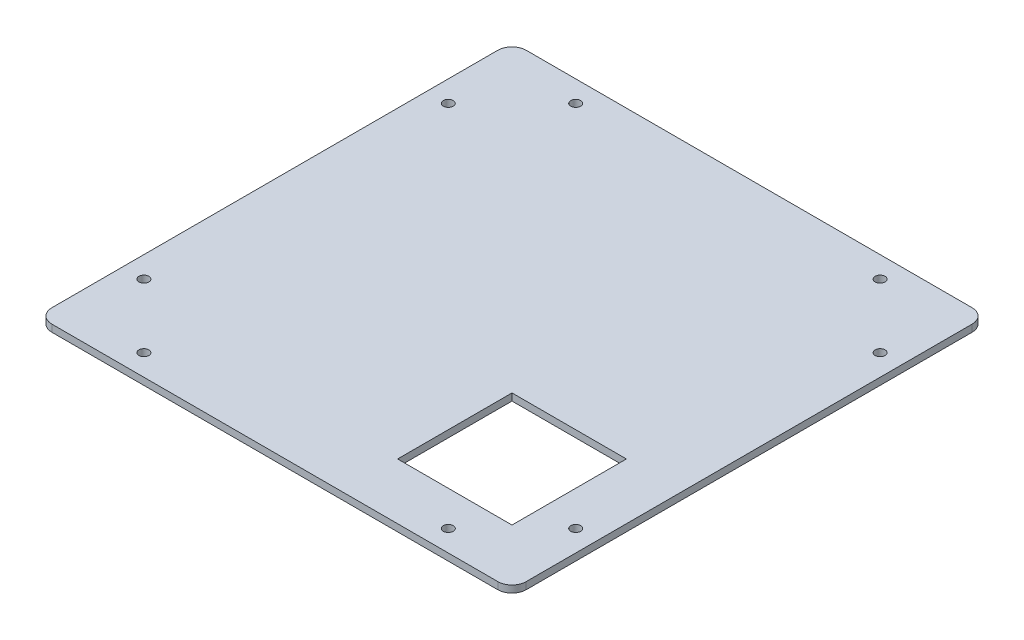
SolidWorks part; units mm, degrees
material "Acrylic (Medium-high impact)"
ref_plane "Front Plane" through (0, 0, 0) normal (0, 0, 1) x (1, 0, 0)
ref_plane "Top Plane" through (0, 0, 0) normal (0, 1, 0) x (1, 0, 0)
ref_plane "Right Plane" through (0, 0, 0) normal (1, 0, 0) x (0, 0, -1)
sketch "Sketch1" plane through (0, 0, 0) normal (0, 1, 0) x (1, 0, 0)
  line L1 (-212.725, -212.725) -> (212.725, -212.725)
  line L2 (-212.725, -212.725) -> (-212.725, 212.725)
  line L3 (-212.725, 212.725) -> (212.725, 212.725)
  line L4 (212.725, -212.725) -> (212.725, 212.725)
  line L5 (-212.725, -212.725) -> (212.725, 212.725) construction
  line L6 (-212.725, 212.725) -> (212.725, -212.725) construction
  point P0 (0, 0)
  dimension "D1" = 425.45
extrude "Boss-Extrude1" add sketch "Sketch1" along normal blind 6.35
sketch "Sketch3" plane through (0, 6.35, 0) normal (0, 1, 0) x (1, 0, 0)
  line L0 (-212.725, 212.725) -> (-212.725, -212.725) construction
  line L1 (-193.675, -193.675) -> (193.675, -193.675) construction
  line L2 (-193.675, -193.675) -> (-193.675, 193.675) construction
  line L3 (-193.675, 193.675) -> (193.675, 193.675) construction
  line L4 (193.675, -193.675) -> (193.675, 193.675) construction
  line L5 (-193.675, -193.675) -> (193.675, 193.675) construction
  line L6 (-193.675, 193.675) -> (193.675, -193.675) construction
  line L7 (212.725, 212.725) -> (-212.725, 212.725) construction
  line L8 (-212.725, -212.725) -> (212.725, -212.725) construction
  line L9 (212.725, -212.725) -> (212.725, 212.725) construction
  circle A0 centre (-193.675, 136.525) radius 8.7312
  circle A1 centre (-193.675, -136.525) radius 8.7312
  circle A2 centre (-136.525, -193.675) radius 8.7312
  circle A3 centre (136.525, -193.675) radius 8.7312
  circle A4 centre (193.675, -136.525) radius 8.7313
  circle A5 centre (193.675, 136.525) radius 8.7312
  circle A6 centre (136.525, 193.675) radius 8.7312
  circle A7 centre (-136.525, 193.675) radius 8.7312
  point P0 (0, 0)
  dimension "D2" = 17.4625
  dimension "D1" = 19.05
  dimension "D3" = 76.2
  dimension "D4" = 76.2
  dimension "D5" = 76.2
  dimension "D6" = 76.2
extrude "Cut-Extrude1" [suppressed] cut sketch "Sketch3" against normal through all
sketch "Sketch4" plane through (0, 6.35, 0) normal (0, 1, 0) x (1, 0, 0)
  line L0 (-212.725, 212.725) -> (-212.725, -212.725) construction
  line L1 (-193.675, -193.675) -> (193.675, -193.675) construction
  line L2 (-193.675, -193.675) -> (-193.675, 193.675) construction
  line L3 (-193.675, 193.675) -> (193.675, 193.675) construction
  line L4 (193.675, -193.675) -> (193.675, 193.675) construction
  line L5 (-193.675, -193.675) -> (193.675, 193.675) construction
  line L6 (-193.675, 193.675) -> (193.675, -193.675) construction
  line L7 (212.725, 212.725) -> (-212.725, 212.725) construction
  line L8 (-212.725, -212.725) -> (212.725, -212.725) construction
  line L9 (212.725, -212.725) -> (212.725, 212.725) construction
  circle A0 centre (-193.675, 136.525) radius 4.445
  circle A1 centre (-193.675, -136.525) radius 4.445
  circle A2 centre (-136.525, -193.675) radius 4.445
  circle A3 centre (136.525, -193.675) radius 4.445
  circle A4 centre (193.675, -136.525) radius 4.445
  circle A5 centre (193.675, 136.525) radius 4.445
  circle A6 centre (136.525, 193.675) radius 4.445
  circle A7 centre (-136.525, 193.675) radius 4.445
  point P0 (0, 0)
  dimension "D2" = 8.89
  dimension "D1" = 19.05
  dimension "D3" = 76.2
  dimension "D4" = 76.2
  dimension "D5" = 76.2
  dimension "D6" = 76.2
extrude "Cut-Extrude2" cut sketch "Sketch4" against normal through all
sketch "Sketch5" plane through (0, 6.35, 0) normal (0, 1, 0) x (1, 0, 0)
  line L0 (-212.725, -212.725) -> (212.725, -212.725) construction
  line L1 (60.325, -60.325) -> (161.925, -60.325) construction
  line L2 (60.325, -60.325) -> (60.325, -161.925) construction
  line L3 (60.325, -161.925) -> (161.925, -161.925) construction
  line L4 (161.925, -60.325) -> (161.925, -161.925) construction
  line L5 (60.325, -60.325) -> (161.925, -161.925) construction
  line L6 (60.325, -161.925) -> (161.925, -60.325) construction
  line L7 (59.817, -59.817) -> (162.433, -59.817)
  line L8 (59.817, -59.817) -> (59.817, -162.433)
  line L9 (59.817, -162.433) -> (162.433, -162.433)
  line L10 (162.433, -59.817) -> (162.433, -162.433)
  line L11 (59.817, -59.817) -> (162.433, -162.433) construction
  line L12 (59.817, -162.433) -> (162.433, -59.817) construction
  line L13 (212.725, -212.725) -> (212.725, 212.725) construction
  point P0 (111.125, -111.125)
  point P5 (111.125, -111.125)
  dimension "D1" = 101.6
  dimension "D2" = 0.508
  dimension "D3" = 101.6
  dimension "D4" = 101.6
extrude "Cut-Extrude3" cut sketch "Sketch5" against normal through all
fillet "Fillet1" radius 12.7 4 edges at (212.725, 3.175, 212.725) (212.725, 3.175, -212.725) (-212.725, 3.175, -212.725) (-212.725, 3.175, 212.725)
